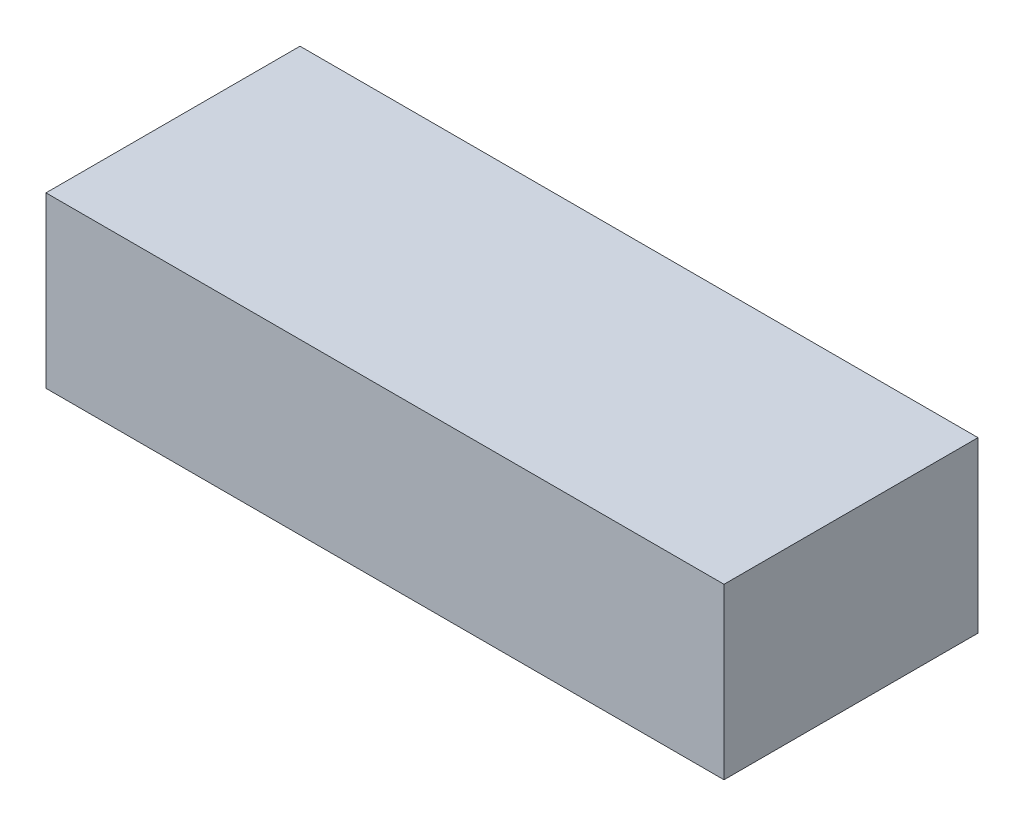
SolidWorks part; units mm, degrees
ref_plane "Front Plane" through (0, 0, 0) normal (0, 0, 1) x (1, 0, 0)
ref_plane "Top Plane" through (0, 0, 0) normal (0, 1, 0) x (1, 0, 0)
ref_plane "Right Plane" through (0, 0, 0) normal (1, 0, 0) x (0, 0, -1)
sketch "Sketch1" plane through (0, 0, 0) normal (0, 1, 0) x (1, 0, 0)
  line L1 (0, 0) -> (9770, 0)
  line L2 (0, 0) -> (0, -3660)
  line L3 (0, -3660) -> (9770, -3660)
  line L4 (9770, 0) -> (9770, -3660)
  dimension "D1" = 9770
  dimension "D2" = 3660
extrude "Boss-Extrude1" add sketch "Sketch1" along normal blind 2440 contours L2 L3 L4 L1
